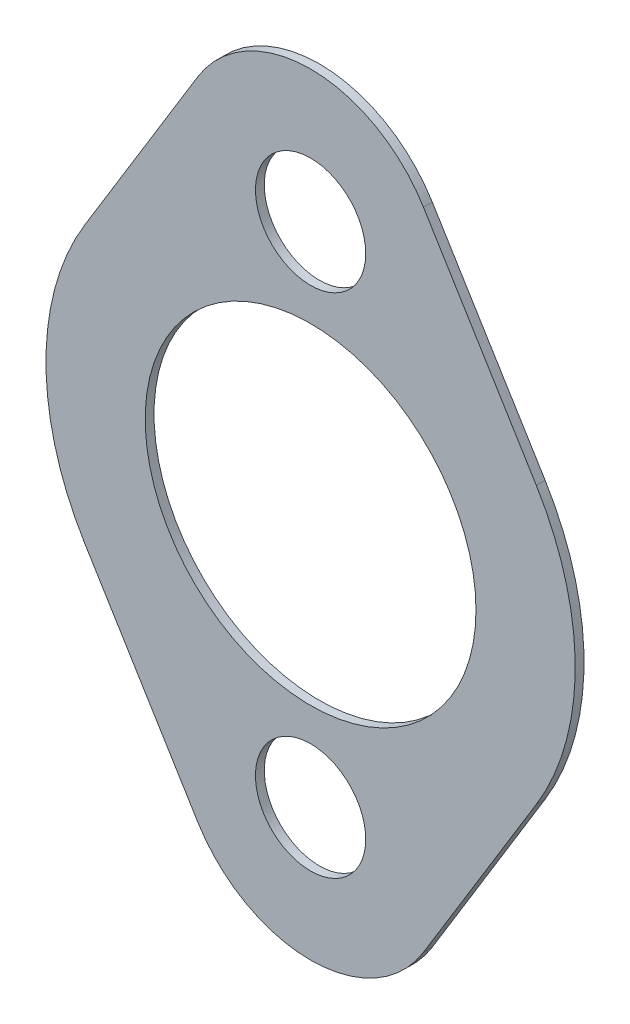
SolidWorks part; units mm, degrees
material "PW20:29:Sc:0:"
ref_plane "Front" through (0, 0, 0) normal (0, 0, 1) x (1, 0, 0)
ref_plane "Top" through (0, 0, 0) normal (0, 1, 0) x (1, 0, 0)
ref_plane "Right" through (0, 0, 0) normal (1, 0, 0) x (0, 0, -1)
sketch "Sketch1" plane through (0, 0, 0) normal (0, 0, 1) x (1, 0, 0)
  line L0 (0, 0) -> (0, 94.4945) construction
  line L1 (0, 0) -> (88.837, 0) construction
  line L2 (25.5932, 73.1522) -> (51.1863, 31.3043)
  line L3 (25.5932, -73.1522) -> (51.1863, -31.3043)
  line L4 (-25.5932, 73.1522) -> (-51.1863, 31.3043)
  line L5 (-25.5932, -73.1522) -> (-51.1863, -31.3043)
  arc A0 (-25.5932, 73.1522) -> (25.5932, 73.1522) centre (0, 57.5) cw
  arc A1 (-25.5932, -73.1522) -> (25.5932, -73.1522) centre (0, -57.5) ccw
  arc A2 (51.1863, 31.3043) -> (51.1863, -31.3043) centre (0, 0) cw
  arc A3 (-51.1863, -31.3043) -> (-51.1863, 31.3043) centre (0, 0) cw
  dimension "EndR" = 30
  dimension "SideR" = 60
  dimension "CtoC" = 115
extrude "Main" add sketch "Sketch1" along normal blind 2
sketch "Sketch2" plane through (0, 0, 2) normal (0, 0, 1) x (1, 0, 0)
  circle A0 centre (0, 57.5) radius 12.5
  circle A1 centre (0, -57.5) radius 12.5
  circle A2 centre (0, 0) radius 37.5
  dimension "BoltH" = 25
  dimension "CenterH" = 75
extrude "Holes" cut sketch "Sketch2" against normal through all
